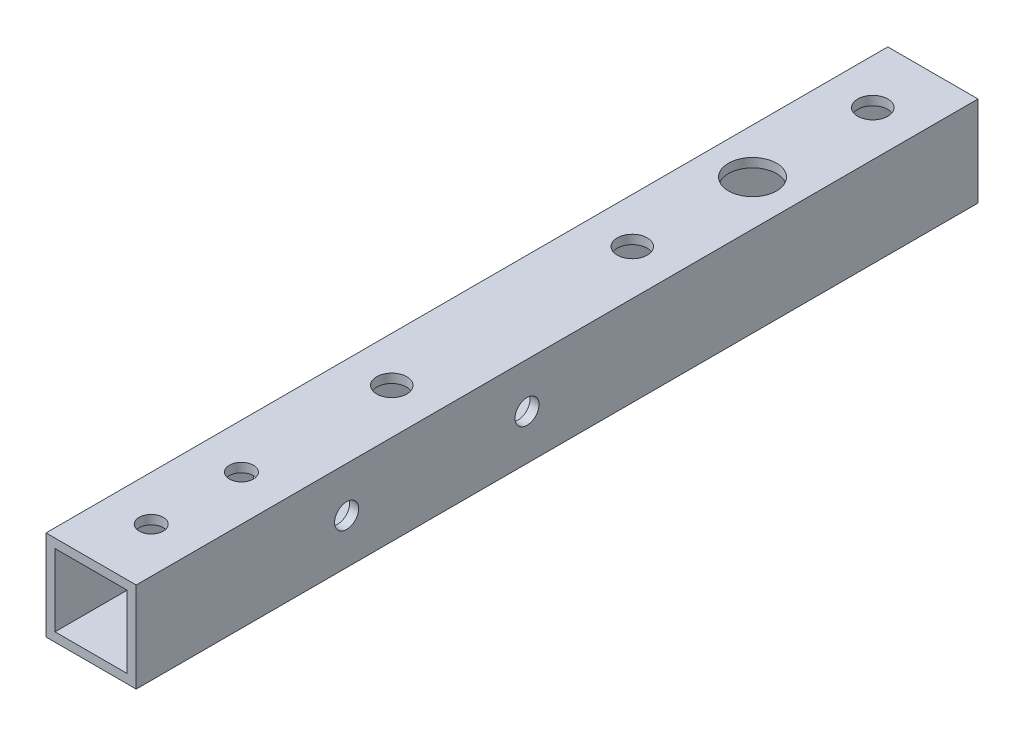
SolidWorks part; units mm, degrees
ref_plane "前视基准面" through (0, 0, 0) normal (0, 0, 1) x (1, 0, 0)
ref_plane "上视基准面" through (0, 0, 0) normal (0, 1, 0) x (1, 0, 0)
ref_plane "右视基准面" through (0, 0, 0) normal (1, 0, 0) x (0, 0, -1)
sketch "草图1" plane through (0, 0, 0) normal (0, 0, 1) x (1, 0, 0)
  line L1 (-6, 6) -> (6, 6)
  line L2 (-6, 6) -> (-6, -6)
  line L3 (-6, -6) -> (6, -6)
  line L4 (6, 6) -> (6, -6)
  line L5 (-6, 6) -> (6, -6) construction
  line L6 (-6, -6) -> (6, 6) construction
  line L7 (-7.5, -7.5) -> (7.5, -7.5)
  line L8 (-7.5, -7.5) -> (-7.5, 7.5)
  line L9 (-7.5, 7.5) -> (7.5, 7.5)
  line L10 (7.5, -7.5) -> (7.5, 7.5)
  line L11 (-7.5, -7.5) -> (7.5, 7.5) construction
  line L12 (-7.5, 7.5) -> (7.5, -7.5) construction
  point P0 (0, 0)
  point P5 (0, 0)
  dimension "D1" = 15
  dimension "D2" = 15
  dimension "D3" = 1.5
  dimension "D4" = 1.5
extrude "凸台-拉伸1" add sketch "草图1" along normal blind 140
sketch "草图3" plane through (0, 7.5, 0) normal (0, 1, 0) x (1, 0, 0)
  line L0 (7.5, 0) -> (-7.5, 0) construction
  circle A0 centre (0, -30) radius 4
  dimension "D1" = 30
  dimension "D2" = 8
extrude "切除-拉伸1" cut sketch "草图3" against normal blind 22
sketch "草图4" plane through (0, -7.5, 0) normal (0, -1, 0) x (1, 0, 0)
  line L0 (-7.5, 140) -> (7.5, 140) construction
  circle A0 centre (0, 130) radius 2
  circle A1 centre (0, 115) radius 2
  dimension "D1" = 4
  dimension "D2" = 10
  dimension "D3" = 25
extrude "切除-拉伸2" cut sketch "草图4" against normal blind 75
sketch "草图5" plane through (7.5, 0, 0) normal (1, 0, 0) x (0, 0, -1)
  line L0 (0, 0) -> (-267.865, 0) construction
  line L1 (-140, -7.5) -> (-140, 7.5) construction
  circle A0 centre (-105, 0) radius 2
  circle A1 centre (-75, 0) radius 2
  dimension "D1" = 4
  dimension "D2" = 35
  dimension "D3" = 30
extrude "切除-拉伸3" cut sketch "草图5" against normal blind 24
sketch "草图6" plane through (0, -7.5, 0) normal (0, -1, 0) x (1, 0, 0)
  line L0 (0, 30) -> (23.0309, 30) construction
  line L1 (0, 50) -> (0, 30) construction
  circle A0 centre (0, 50) radius 2.5
  circle A2 centre (0, 10) radius 2.5
  dimension "D1" = 5
  dimension "D2" = 40
extrude "切除-拉伸4" cut sketch "草图6" against normal through all
sketch "草图7" plane through (0, 7.5, 0) normal (0, 1, 0) x (1, 0, 0)
  line L0 (-7.5, -77) -> (-7.5, -103) construction
  line L2 (-7.5, -90) -> (24.2643, -90) construction
  circle A1 centre (0, -90) radius 2.5
  point P2 (0, 0)
  dimension "D1" = 5
extrude "切除-拉伸5" cut sketch "草图7" against normal through all
